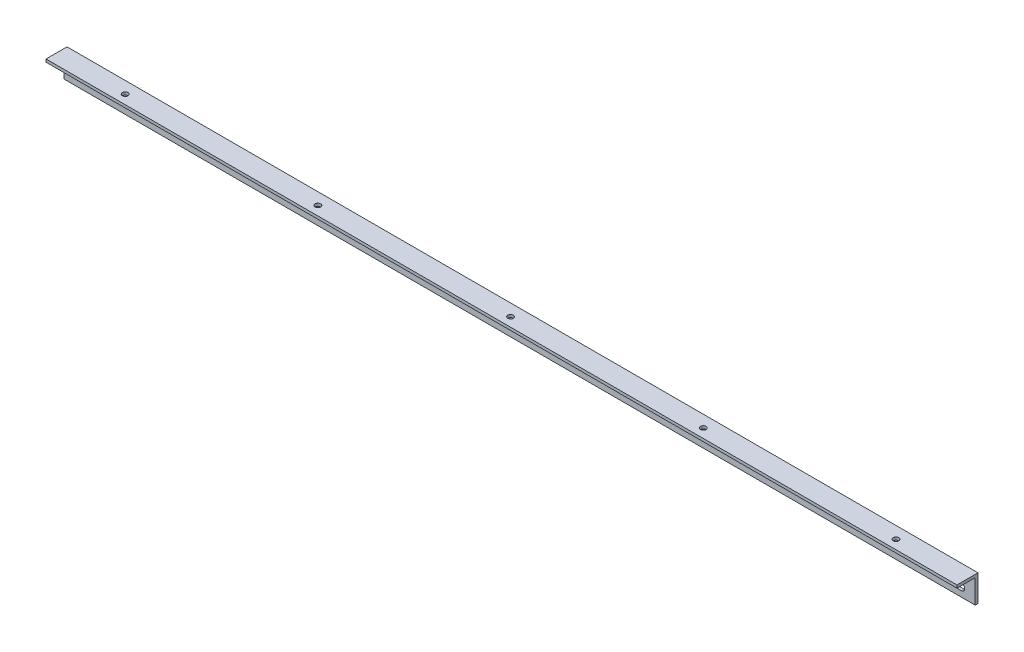
SolidWorks part; units mm, degrees
material "1060 Alloy"
ref_plane "Front Plane" through (0, 0, 0) normal (0, 0, 1) x (1, 0, 0)
ref_plane "Top Plane" through (0, 0, 0) normal (0, 1, 0) x (1, 0, 0)
ref_plane "Right Plane" through (0, 0, 0) normal (1, 0, 0) x (0, 0, -1)
sketch "Sketch1" plane through (0, 0, 0) normal (1, 0, 0) x (0, 0, -1)
  line L0 (0, 0) -> (-15, 0)
  line L1 (-15, 0) -> (-15, -2)
  line L2 (-15, -2) -> (-2, -2)
  line L3 (-2, -2) -> (-2, -19)
  line L4 (-2, -19) -> (0, -19)
  line L5 (0, -19) -> (0, 0)
  dimension "D1" = 15
  dimension "D2" = 2
  dimension "D3" = 2
  dimension "D4" = 19
extrude "Boss-Extrude1" add sketch "Sketch1" along normal blind 650
sketch "Sketch3" plane through (0, 0, 0) normal (0, 0, -1) x (-1, 0, 0)
  line L0 (-640, -12.5) -> (-10, -12.5) construction
  line L3 (-650, -19) -> (0, -19) construction
  line L4 (-10, -19) -> (-10, 0) construction
  line L5 (-650, 0) -> (0, 0) construction
  line L6 (-640, -19) -> (-640, 0) construction
  line L7 (-640, -12.5) -> (-650, -12.5) construction
  line L8 (-650, -19) -> (-650, 0) construction
  line L9 (-10, -12.5) -> (0, -12.5) construction
  line L10 (0, -19) -> (0, 0) construction
  line L11 (-640, -12.5) -> (-10, -12.5) construction
  line L12 (-640, -10) -> (-10, -10)
  line L13 (-640, -15) -> (-10, -15)
  arc A0 (-640, -10) -> (-640, -15) centre (-640, -12.5) ccw
  arc A1 (-10, -15) -> (-10, -10) centre (-10, -12.5) ccw
  point P1 (-325, -12.5)
  dimension "D1" = 6.5
  dimension "D2" = 10
  dimension "D3" = 5
extrude "Cut-Extrude1" cut sketch "Sketch3" against normal up to surface (2 mm away) up to face at (325, -10.5, 2)
sketch "Sketch4" plane through (0, -2, 0) normal (0, -1, 0) x (1, 0, 0)
  line L0 (50, 8.5) -> (600, 8.5) construction
  line L1 (50, 15) -> (600, 2) construction
  line L2 (50, 2) -> (600, 15) construction
  line L3 (50, 15) -> (50, 2) construction
  line L4 (650, 15) -> (0, 15) construction
  line L5 (650, 2) -> (0, 2) construction
  line L6 (600, 15) -> (600, 2) construction
  line L7 (50, 8.5) -> (0, 8.5) construction
  line L8 (0, 15) -> (0, 2) construction
  line L9 (600, 8.5) -> (650, 8.5) construction
  line L10 (650, 15) -> (650, 2) construction
  line L11 (325, 8.5) -> (325, 15) construction
  line L12 (325, 8.5) -> (325, 2) construction
  line L13 (325, 15) -> (50, 2) construction
  line L14 (50, 15) -> (325, 2) construction
  line L15 (325, 15) -> (600, 2) construction
  line L16 (325, 2) -> (600, 15) construction
  circle A0 centre (325, 8.5) radius 2
  circle A1 centre (187.5, 8.5) radius 2
  circle A2 centre (50, 8.5) radius 2
  circle A3 centre (462.5, 8.5) radius 2
  circle A4 centre (600, 8.5) radius 2
  dimension "D2" = 4
  dimension "D1" = 50
extrude "Cut-Extrude2" cut sketch "Sketch4" against normal up to surface (2 mm away) up to face at (325, 0, 7.5)
equation "\"StrutLength\"=750"
equation "\"D1@Boss-Extrude1\"= \"StrutLength\" - \"StrutJointMargin\" * 2"
equation "\"StrutJointMargin\"= 50"
equation "\"StrutWidth\"=15"
equation "\"D1@Sketch1\"=\"StrutWidth\""
